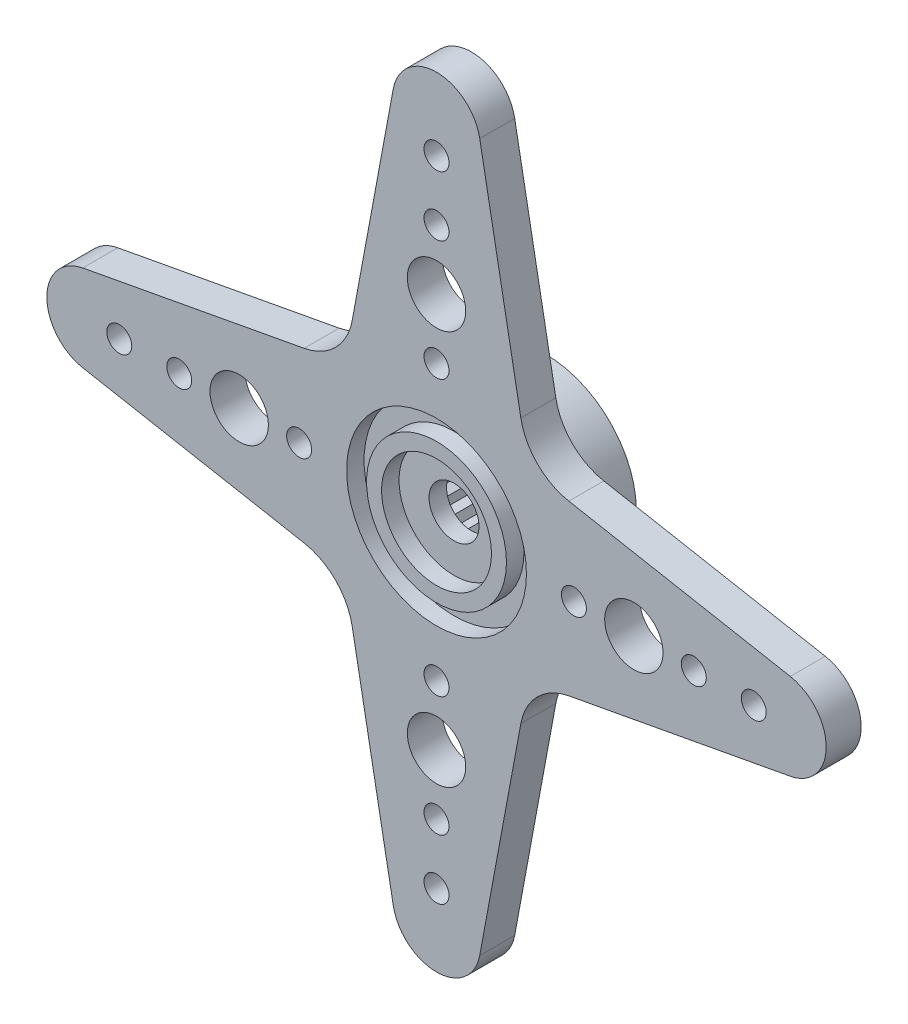
SolidWorks part; units mm, degrees
ref_plane "Front Plane" through (0, 0, 0) normal (0, 0, 1) x (1, 0, 0)
ref_plane "Top Plane" through (0, 0, 0) normal (0, 1, 0) x (1, 0, 0)
ref_plane "Right Plane" through (0, 0, 0) normal (1, 0, 0) x (0, 0, -1)
sketch "Sketch1" plane through (0, 0, 0) normal (0, 0, 1) x (1, 0, 0)
  line L50 (-10.25, 3) -> (-10.5946, 2.7283)
  line L51 (-10.5946, 2.7283) -> (-10.996, 2.9057)
  line L52 (-10.996, 2.9057) -> (-11.2623, 2.5569)
  line L53 (-11.2623, 2.5569) -> (-11.6952, 2.6289)
  line L54 (-11.6952, 2.6289) -> (-11.8664, 2.2248)
  line L55 (-11.8664, 2.2248) -> (-12.3036, 2.1869)
  line L56 (-12.3036, 2.1869) -> (-12.3689, 1.7529)
  line L57 (-12.3689, 1.7529) -> (-12.7829, 1.6075)
  line L58 (-12.7829, 1.6075) -> (-12.7382, 1.1709)
  line L59 (-12.7382, 1.1709) -> (-13.1031, 0.927)
  line L60 (-13.1031, 0.927) -> (-12.9512, 0.5153)
  line L61 (-12.9512, 0.5153) -> (-13.244, 0.1884)
  line L62 (-13.244, 0.1884) -> (-12.9945, -0.1727)
  line L63 (-12.9945, -0.1727) -> (-13.1968, -0.5621)
  line L64 (-13.1968, -0.5621) -> (-12.8654, -0.8498)
  line L65 (-12.8654, -0.8498) -> (-12.9644, -1.2773)
  line L66 (-12.9644, -1.2773) -> (-12.5719, -1.4735)
  line L67 (-12.5719, -1.4735) -> (-12.5615, -1.9123)
  line L68 (-12.5615, -1.9123) -> (-12.1325, -2.0047)
  line L69 (-12.1325, -2.0047) -> (-12.0133, -2.427)
  line L70 (-12.0133, -2.427) -> (-11.5748, -2.4098)
  line L71 (-11.5748, -2.4098) -> (-11.3543, -2.7893)
  line L72 (-11.3543, -2.7893) -> (-10.9339, -2.6636)
  line L73 (-10.9339, -2.6636) -> (-10.626, -2.9763)
  line L74 (-10.626, -2.9763) -> (-10.25, -2.75)
  line L75 (-10.25, -2.75) -> (-9.874, -2.9763)
  line L76 (-9.874, -2.9763) -> (-9.5661, -2.6636)
  line L77 (-9.5661, -2.6636) -> (-9.1456, -2.7893)
  line L78 (-9.1456, -2.7893) -> (-8.9251, -2.4098)
  line L79 (-8.9251, -2.4098) -> (-8.4866, -2.427)
  line L80 (-8.4866, -2.427) -> (-8.3675, -2.0047)
  line L81 (-8.3675, -2.0047) -> (-7.9384, -1.9123)
  line L82 (-7.9384, -1.9123) -> (-7.9281, -1.4735)
  line L83 (-7.9281, -1.4735) -> (-7.5355, -1.2773)
  line L84 (-7.5355, -1.2773) -> (-7.6346, -0.8498)
  line L85 (-7.6346, -0.8498) -> (-7.3031, -0.5621)
  line L86 (-7.3031, -0.5621) -> (-7.5054, -0.1727)
  line L87 (-7.5054, -0.1727) -> (-7.2559, 0.1884)
  line L88 (-7.2559, 0.1884) -> (-7.5487, 0.5153)
  line L89 (-7.5487, 0.5153) -> (-7.3968, 0.927)
  line L90 (-7.3968, 0.927) -> (-7.7617, 1.1709)
  line L91 (-7.7617, 1.1709) -> (-7.717, 1.6075)
  line L92 (-7.717, 1.6075) -> (-8.1311, 1.7529)
  line L93 (-8.1311, 1.7529) -> (-8.1963, 2.1869)
  line L94 (-8.1963, 2.1869) -> (-8.6336, 2.2248)
  line L95 (-8.6336, 2.2248) -> (-8.8047, 2.6289)
  line L96 (-8.8047, 2.6289) -> (-9.2376, 2.5569)
  line L97 (-9.2376, 2.5569) -> (-9.5039, 2.9057)
  line L98 (-9.5039, 2.9057) -> (-9.9053, 2.7283)
  line L99 (-9.9053, 2.7283) -> (-10.25, 3)
  line L100 (-10.25, 3) -> (-10.5946, 2.7283)
  line L101 (-10.5946, 2.7283) -> (-10.996, 2.9057)
  line L102 (-10.996, 2.9057) -> (-11.2623, 2.5569)
  line L103 (-11.2623, 2.5569) -> (-11.6952, 2.6289)
  line L104 (-11.6952, 2.6289) -> (-11.8664, 2.2248)
  line L105 (-11.8664, 2.2248) -> (-12.3036, 2.1869)
  line L106 (-12.3036, 2.1869) -> (-12.3689, 1.7529)
  line L107 (-12.3689, 1.7529) -> (-12.7829, 1.6075)
  line L108 (-12.7829, 1.6075) -> (-12.7382, 1.1709)
  line L109 (-12.7382, 1.1709) -> (-13.1031, 0.927)
  line L110 (-13.1031, 0.927) -> (-12.9512, 0.5153)
  line L111 (-12.9512, 0.5153) -> (-13.244, 0.1884)
  line L112 (-13.244, 0.1884) -> (-12.9945, -0.1727)
  line L113 (-12.9945, -0.1727) -> (-13.1968, -0.5621)
  line L114 (-13.1968, -0.5621) -> (-12.8654, -0.8498)
  line L115 (-12.8654, -0.8498) -> (-12.9644, -1.2773)
  line L116 (-12.9644, -1.2773) -> (-12.5719, -1.4735)
  line L117 (-12.5719, -1.4735) -> (-12.5615, -1.9123)
  line L118 (-12.5615, -1.9123) -> (-12.1325, -2.0047)
  line L119 (-12.1325, -2.0047) -> (-12.0133, -2.427)
  line L120 (-12.0133, -2.427) -> (-11.5748, -2.4098)
  line L121 (-11.5748, -2.4098) -> (-11.3543, -2.7893)
  line L122 (-11.3543, -2.7893) -> (-10.9339, -2.6636)
  line L123 (-10.9339, -2.6636) -> (-10.626, -2.9763)
  line L124 (-10.626, -2.9763) -> (-10.25, -2.75)
  line L125 (-10.25, -2.75) -> (-9.874, -2.9763)
  line L126 (-9.874, -2.9763) -> (-9.5661, -2.6636)
  line L127 (-9.5661, -2.6636) -> (-9.1456, -2.7893)
  line L128 (-9.1456, -2.7893) -> (-8.9251, -2.4098)
  line L129 (-8.9251, -2.4098) -> (-8.4866, -2.427)
  line L130 (-8.4866, -2.427) -> (-8.3675, -2.0047)
  line L131 (-8.3675, -2.0047) -> (-7.9384, -1.9123)
  line L132 (-7.9384, -1.9123) -> (-7.9281, -1.4735)
  line L133 (-7.9281, -1.4735) -> (-7.5355, -1.2773)
  line L134 (-7.5355, -1.2773) -> (-7.6346, -0.8498)
  line L135 (-7.6346, -0.8498) -> (-7.3031, -0.5621)
  line L136 (-7.3031, -0.5621) -> (-7.5054, -0.1727)
  line L137 (-7.5054, -0.1727) -> (-7.2559, 0.1884)
  line L138 (-7.2559, 0.1884) -> (-7.5487, 0.5153)
  line L139 (-7.5487, 0.5153) -> (-7.3968, 0.927)
  line L140 (-7.3968, 0.927) -> (-7.7617, 1.1709)
  line L141 (-7.7617, 1.1709) -> (-7.717, 1.6075)
  line L142 (-7.717, 1.6075) -> (-8.1311, 1.7529)
  line L143 (-8.1311, 1.7529) -> (-8.1963, 2.1869)
  line L144 (-8.1963, 2.1869) -> (-8.6336, 2.2248)
  line L145 (-8.6336, 2.2248) -> (-8.8047, 2.6289)
  line L146 (-8.8047, 2.6289) -> (-9.2376, 2.5569)
  line L147 (-9.2376, 2.5569) -> (-9.5039, 2.9057)
  line L148 (-9.5039, 2.9057) -> (-9.9053, 2.7283)
  line L149 (-9.9053, 2.7283) -> (-10.25, 3)
  circle A0 centre (-10.25, 0) radius 4.5
  dimension "D2" = 9
  dimension "D1" = 0
extrude "Boss-Extrude1" add sketch "Sketch1" against normal blind 3.75 contours A0 L149 L148 L147 L146 L145 L144 L143 L142 L141 L140 L139 L138 L137 L136 L135 L134 L133 L132 L131 L130 L129 L128 L127 L126 L125 L124 L123 L122 L121 L120 L119 L118 L117 L116 L115 L114 L113 L112 L111 L110 L109 L108 L107 L106 L105 L104 L103 L102 L101
sketch "Sketch2" plane through (0, 0, 0) normal (0, 0, 1) x (1, 0, 0)
  circle A0 centre (-10.25, 0) radius 1.25
  circle A1 centre (-10.25, 0) radius 3.5
  circle A2 centre (-10.25, 0) radius 4.5
  dimension "D1" = 7
  dimension "D2" = 2.5
  dimension "D3" = 9
extrude "Boss-Extrude2" add sketch "Sketch2" along normal blind 1.75 contours A2 A1 | A1 A0
sketch "Sketch4" plane through (0, 0, 1.75) normal (0, 0, 1) x (1, 0, 0)
  circle A0 centre (-10.25, 0) radius 3.5
  circle A1 centre (-10.25, 0) radius 2.75
  circle M2 centre (-10.25, 0) radius 1.25
  dimension "D1" = 7
  dimension "D2" = 0.75
extrude "Cut-Extrude1" cut sketch "Sketch4" against normal blind 0.875 contours A1 M2
sketch "Sketch6" plane through (0, 0, 1.75) normal (0, 0, 1) x (1, 0, 0)
  circle A0 centre (-10.25, 0) radius 3.5
  circle A1 centre (-10.25, 0) radius 2.75 construction
  circle A2 centre (-10.25, 0) radius 4.5
  circle M2 centre (-10.25, 0) radius 4.5
  dimension "D1" = 0.75
  dimension "D2" = 9
extrude "Cut-Extrude2" cut sketch "Sketch6" against normal blind 0.875 contours A0 M2
sketch "Sketch7" [suppressed] plane through (0, 0, 1.75) normal (0, 0, 1) x (1, 0, 0)
  circle A0 centre (-10.25, 0) radius 10.5
  circle A1 centre (-10.25, 0) radius 4.5
  dimension "D1" = 21
extrude "Boss-Extrude3" [suppressed] add sketch "Sketch7" against normal blind 1.75
sketch "Sketch9" [suppressed] plane through (0, 0, 1.75) normal (0, 0, 1) x (1, 0, 0)
  line L0 (-10.25, 0) -> (-10.25, 11.6833) construction
  circle A0 centre (-10.25, 7.875) radius 0.625
  circle A1 centre (-14.125, 7.875) radius 0.625
  circle A2 centre (-10.25, 0) radius 10.5 construction
  circle A3 centre (-6.375, 7.875) radius 0.625
  dimension "D1" = 2
  dimension "D2" = 1.25
  dimension "D3" = 1.25
  dimension "D4" = 2.625
extrude "Cut-Extrude3" [suppressed] cut sketch "Sketch9" against normal through all
pattern_circular "CirPattern1" [suppressed] count 4 over 360
chamfer "Chamfer1" [suppressed] distance 1 angle 30
sketch "Sketch10" plane through (0, 0, 1.75) normal (0, 0, 1) x (1, 0, 0)
  line L0 (-10.25, 0) -> (-10.25, 9.0053) construction
  line L1 (-10.25, 0) -> (0.0732, 10.3232) construction
  line L2 (-10.25, 0) -> (1.1009, 0) construction
  line L3 (-8.0869, 17.7016) -> (-6.0299, 6.622)
  line L4 (-3.6279, 4.2201) -> (7.4516, 2.163)
  line L5 (7.4516, -2.163) -> (-3.6279, -4.2201)
  line L6 (-6.0299, -6.622) -> (-8.0869, -17.7016)
  line L7 (-12.413, -17.7016) -> (-14.47, -6.622)
  line L8 (-16.872, -4.2201) -> (-27.9515, -2.163)
  line L9 (-27.9515, 2.163) -> (-16.872, 4.2201)
  line L10 (-14.47, 6.622) -> (-12.413, 17.7016)
  arc A0 (-8.0869, 17.7016) -> (-10.25, 19.5) centre (-10.25, 17.3) ccw
  arc A1 (7.4516, -2.163) -> (7.4516, 2.163) centre (7.05, 0) ccw
  arc A2 (-6.0299, 6.622) -> (-3.6279, 4.2201) centre (-3.0803, 7.1697) ccw
  circle A3 centre (-10.25, 15.875) radius 0.625
  circle A4 centre (-10.25, 12.875) radius 0.625
  circle A5 centre (-10.25, 9.875) radius 0.625
  circle A6 centre (-10.25, 6.875) radius 0.625
  arc A7 (7.4516, -2.163) -> (9.25, 0) centre (7.05, 0) ccw
  circle A8 centre (5.625, 0) radius 0.625
  circle A9 centre (2.625, 0) radius 0.625
  circle A10 centre (-0.375, 0) radius 0.625
  circle A11 centre (-3.375, 0) radius 0.625
  arc A12 (-3.6279, -4.2201) -> (-6.0299, -6.622) centre (-3.0803, -7.1697) ccw
  arc A13 (-12.413, -17.7016) -> (-8.0869, -17.7016) centre (-10.25, -17.3) ccw
  arc A14 (-12.413, -17.7016) -> (-10.25, -19.5) centre (-10.25, -17.3) ccw
  circle A15 centre (-10.25, -15.875) radius 0.625
  circle A16 centre (-10.25, -12.875) radius 0.625
  circle A17 centre (-10.25, -9.875) radius 0.625
  circle A18 centre (-10.25, -6.875) radius 0.625
  arc A19 (-14.47, -6.622) -> (-16.872, -4.2201) centre (-17.4196, -7.1697) ccw
  arc A20 (-27.9515, 2.163) -> (-27.9515, -2.163) centre (-27.5499, 0) ccw
  arc A21 (-27.9515, 2.163) -> (-29.7499, 0) centre (-27.5499, 0) ccw
  circle A22 centre (-26.1249, 0) radius 0.625
  circle A23 centre (-23.1249, 0) radius 0.625
  circle A24 centre (-20.1249, 0) radius 0.625
  circle A25 centre (-17.1249, 0) radius 0.625
  arc A26 (-16.872, 4.2201) -> (-14.47, 6.622) centre (-17.4196, 7.1697) ccw
  arc A27 (-8.0869, 17.7016) -> (-12.413, 17.7016) centre (-10.25, 17.3) ccw
  circle A28 centre (-10.25, 0) radius 4.5
  point P1 (-10.25, 0)
  point P10 (-5.6538, 4.5962)
  point P20 (-5.6538, 4.5962)
  point P21 (-10.25, 19.5)
  point P84 (-10.25, 0)
  circle M4 centre (-10.25, 0) radius 3.5
  dimension "D2" = 19.5
  dimension "D3" = 19.5
  dimension "D4" = 4.4
  dimension "D5" = 4.4
  dimension "D7" = 3
  dimension "D8" = 1.25
  dimension "D9" = 3
  dimension "D1" = 45
  dimension "D6" = 6.5
  dimension "D10" = 4
  dimension "D11" = 4
extrude "Boss-Extrude4" add sketch "Sketch10" against normal blind 1.75 contours A0 A27 L10 A26 L9 A20 L8 A19 L7 A13 L6 A12 L5 A1 L4 A2 L3 A3 A4 A5 A6 A8 A9 A10 A11 A15 A16 A17 A18 A22 A23 M4
chamfer "Chamfer2" distance 1 angle 30 1 edges at (-5.75, 0, 0)
sketch "Sketch11" [suppressed] plane through (0, 0, 1.75) normal (0, 0, 1) x (1, 0, 0)
  line L0 (-10.25, 0) -> (-10.25, 17.5605) construction
  line L1 (-10.25, 0) -> (4.9579, 8.7803) construction
  line L2 (-10.25, 0) -> (4.9579, -8.7803) construction
  line L3 (-10.25, 0) -> (-10.25, -17.5605) construction
  line L4 (-10.25, 0) -> (-25.4578, -8.7803) construction
  line L5 (-10.25, 0) -> (-25.4578, 8.7803) construction
  line L6 (-10.25, 0) -> (-3.969, 10.8789) construction
  line L7 (-10.25, 0) -> (2.312, 0) construction
  line L8 (-10.25, 0) -> (-3.969, -10.8789) construction
  line L9 (-10.25, 0) -> (-16.5309, -10.8789) construction
  line L10 (-10.25, 0) -> (-22.8119, 0) construction
  line L11 (-10.25, 0) -> (-16.5309, 10.8789) construction
  line L12 (-8.5769, 14.5133) -> (-6.25, 6.9282)
  line L13 (-6.25, 6.9282) -> (1.4824, 8.7055)
  line L14 (3.1554, 5.8077) -> (-2.25, 0)
  line L15 (-2.25, 0) -> (3.1554, -5.8077)
  line L16 (1.4824, -8.7055) -> (-6.25, -6.9282)
  line L17 (-6.25, -6.9282) -> (-8.5769, -14.5133)
  line L18 (-11.923, -14.5133) -> (-14.25, -6.9282)
  line L19 (-14.25, -6.9282) -> (-21.9823, -8.7055)
  line L20 (-23.6553, -5.8077) -> (-18.25, 0)
  line L21 (-18.25, 0) -> (-23.6553, 5.8077)
  line L22 (-21.9823, 8.7055) -> (-14.25, 6.9282)
  line L23 (-14.25, 6.9282) -> (-11.923, 14.5133)
  circle A0 centre (-10.25, 0) radius 4.5
  arc A1 (-8.5769, 14.5133) -> (-10.25, 15.75) centre (-10.25, 14) ccw
  arc A2 (3.3899, 7.875) -> (1.4824, 8.7055) centre (1.8744, 7) ccw
  circle A4 centre (-10.25, 13.375) radius 0.625
  circle A5 centre (-10.25, 10.375) radius 0.625
  circle A6 centre (-10.25, 7.375) radius 0.625
  circle A7 centre (1.3331, 6.6875) radius 0.625
  arc A8 (3.1554, 5.8077) -> (3.3899, 7.875) centre (1.8744, 7) ccw
  circle A9 centre (-1.2649, 5.1875) radius 0.625
  circle A10 centre (-3.863, 3.6875) radius 0.625
  arc A11 (3.3899, -7.875) -> (3.1554, -5.8077) centre (1.8744, -7) ccw
  circle A12 centre (1.3331, -6.6875) radius 0.625
  arc A13 (1.4824, -8.7055) -> (3.3899, -7.875) centre (1.8744, -7) ccw
  circle A14 centre (-1.2649, -5.1875) radius 0.625
  circle A15 centre (-3.863, -3.6875) radius 0.625
  arc A16 (-10.25, -15.75) -> (-8.5769, -14.5133) centre (-10.25, -14) ccw
  circle A17 centre (-10.25, -13.375) radius 0.625
  arc A18 (-11.923, -14.5133) -> (-10.25, -15.75) centre (-10.25, -14) ccw
  circle A19 centre (-10.25, -10.375) radius 0.625
  circle A20 centre (-10.25, -7.375) radius 0.625
  arc A21 (-23.8899, -7.875) -> (-21.9823, -8.7055) centre (-22.3743, -7) ccw
  circle A22 centre (-21.833, -6.6875) radius 0.625
  arc A23 (-23.6553, -5.8077) -> (-23.8899, -7.875) centre (-22.3743, -7) ccw
  circle A24 centre (-19.235, -5.1875) radius 0.625
  circle A25 centre (-16.6369, -3.6875) radius 0.625
  arc A26 (-23.8899, 7.875) -> (-23.6553, 5.8077) centre (-22.3743, 7) ccw
  circle A27 centre (-21.833, 6.6875) radius 0.625
  arc A28 (-21.9823, 8.7055) -> (-23.8899, 7.875) centre (-22.3743, 7) ccw
  circle A29 centre (-19.235, 5.1875) radius 0.625
  circle A30 centre (-16.6369, 3.6875) radius 0.625
  arc A31 (-10.25, 15.75) -> (-11.923, 14.5133) centre (-10.25, 14) ccw
  point P5 (-10.25, 0)
  point P12 (-10.25, 0)
  point P20 (-10.25, 0)
  point P22 (-6.25, 6.9282)
  point P26 (-10.25, 15.75)
  point P27 (3.3899, 7.875)
  point P102 (-10.25, 0)
  dimension "D4" = 15.75
  dimension "D5" = 15.75
  dimension "D6" = 3.5
  dimension "D7" = 3.5
  dimension "D9" = 1.25
  dimension "D10" = 1.75
  dimension "D2" = 30
  dimension "D8" = 8
  dimension "D11" = 3
  dimension "D1" = 6
  dimension "D3" = 6
  dimension "D12" = 6
extrude "Boss-Extrude5" [suppressed] add sketch "Sketch11" against normal blind 1.75 contours A1 A31 L23 L22 A28 A26 L21 L20 A23 A21 L19 L18 A18 A16 L17 L16 A13 A11 L15 L14 A8 A2 L13 L12 A0 A4 A5 A6 A7 A9 A10 A12 A14 A15 A17 A19 A20
chamfer "Chamfer4" [suppressed] distance 1 angle 30
sketch "Sketch12" [suppressed] plane through (0, 0, 0.875) normal (0, 0, 1) x (1, 0, 0)
  circle A0 centre (-10.25, 0) radius 1.25
  circle A1 centre (-10.25, 0) radius 5
extrude "Boss-Extrude6" [suppressed] add sketch "Sketch12" along normal blind 0.125
sketch "Sketch14" [suppressed] plane through (0, 0, 1) normal (0, 0, 1) x (1, 0, 0)
  line L0 (-10.25, 0) -> (-28.2499, 0) construction
  line L1 (-10.25, -6) -> (-28.2499, -6)
  line L2 (-10.25, 6) -> (-28.2499, 6)
  arc A0 (-10.25, -6) -> (-10.25, 6) centre (-10.25, 0) ccw
  arc A1 (-28.2499, 6) -> (-28.2499, -6) centre (-28.2499, 0) ccw
  point P4 (-19.2499, 0)
  dimension "D1" = 12
  dimension "D2" = 29.9999
extrude "Boss-Extrude7" [suppressed] add sketch "Sketch14" along normal blind 3
sketch "Sketch16" [suppressed] plane through (0, 0, 1) normal (0, 0, -1) x (-1, 0, 0)
  line L0 (25.9999, 0) -> (30.4999, 0) construction
  line L1 (25.9999, 2.75) -> (30.4999, 2.75)
  line L2 (25.9999, -2.75) -> (30.4999, -2.75)
  arc A0 (25.9999, 2.75) -> (25.9999, -2.75) centre (25.9999, 0) ccw
  arc A1 (30.4999, -2.75) -> (30.4999, 2.75) centre (30.4999, 0) ccw
  arc A10 (28.2499, -6) -> (28.2499, 6) centre (28.2499, 0) ccw construction
  point P3 (28.2499, 0)
  point P8 (34.2499, 0)
  point P9 (33.2499, 0)
  dimension "D2" = 10
  dimension "D3" = 1
  dimension "D1" = 5.5
extrude "Boss-Extrude8" [suppressed] add sketch "Sketch16" along normal blind 2.75 contours L1 A1 L2 A0
sketch "Sketch17" [suppressed] plane through (0, 0, -1.75) normal (0, 0, -1) x (-1, 0, 0)
  circle A0 centre (30.7499, 0) radius 1.5
  circle A1 centre (25.7499, 0) radius 1.5
  arc A5 (28.2499, -6) -> (28.2499, 6) centre (28.2499, 0) ccw construction
  dimension "D1" = 3
  dimension "D2" = 3
  dimension "D3" = 2
  dimension "D4" = 2
extrude "Cut-Extrude4" [suppressed] cut sketch "Sketch17" against normal through all
sketch "Sketch18" [suppressed] plane through (0, 0, 1) normal (0, 0, -1) x (-1, 0, 0)
  circle A0 centre (10.25, 0) radius 3
  dimension "D1" = 6
extrude "Cut-Extrude5" [suppressed] cut sketch "Sketch18" against normal through all
sketch "Sketch19" [suppressed] plane through (0, 0, 1.5) normal (0, 0, 1) x (1, 0, 0)
  line L0 (-35.7499, 0) -> (15.25, 0) construction
  line L1 (-9.625, 5.9674) -> (14.1146, 3.481)
  line L2 (14.1146, -3.481) -> (-9.625, -5.9674)
  line L3 (-10.25, 0) -> (-10.25, 10.691) construction
  line L4 (-34.6145, -3.481) -> (-10.875, -5.9674)
  line L5 (-10.875, 5.9674) -> (-34.6145, 3.481)
  circle A0 centre (-10.25, 0) radius 6
  arc A1 (14.1146, -3.481) -> (14.1146, 3.481) centre (13.75, 0) ccw
  circle A2 centre (14.625, 0) radius 0.625
  circle A3 centre (11.375, 0) radius 0.625
  circle A4 centre (8.125, 0) radius 0.625
  circle A5 centre (4.875, 0) radius 0.625
  circle A6 centre (1.625, 0) radius 0.625
  circle A7 centre (-22.1249, 0) radius 0.625
  circle A8 centre (-25.3749, 0) radius 0.625
  circle A9 centre (-28.6249, 0) radius 0.625
  circle A10 centre (-31.8749, 0) radius 0.625
  circle A11 centre (-35.1249, 0) radius 0.625
  arc A12 (-34.6145, -3.481) -> (-34.6145, 3.481) centre (-34.2499, 0) cw
  point P37 (-10.25, -6)
  circle M5 centre (-10.25, 0) radius 5
  circle M6 centre (-10.25, 0) radius 1.25
  dimension "D1" = 12
  dimension "D2" = 7
  dimension "D4" = 1.25
  dimension "D5" = 2
  dimension "D3" = 27.4999
  dimension "D6" = 5
extrude "Boss-Extrude9" [suppressed] add sketch "Sketch19" along normal blind 2.5 contours A12 L4 A0 L5 A10 A8 A7 A9 A11 | A0 M5 | M5 M6 | L2 A1 L1 A0 A6 A5 A4 A3 A2
sketch "Sketch20" [suppressed] plane through (0, 0, 4) normal (0, 0, 1) x (1, 0, 0)
  arc A0 (-9.625, 5.9674) -> (-10.875, 5.9674) centre (-10.25, 0) ccw construction
  circle A1 centre (-10.25, 0) radius 4
  circle A2 centre (-10.25, 0) radius 6
  point P5 (-10.25, 4)
  point P7 (-10.25, -4)
  dimension "D1" = 2
extrude "Boss-Extrude10" [suppressed] add sketch "Sketch20" along normal blind 1
sketch "Sketch21" [suppressed] plane through (0, 0, 4) normal (0, 0, 1) x (1, 0, 0)
  circle A0 centre (-10.25, 0) radius 4 construction
  circle A1 centre (-10.25, 0) radius 4
  circle A2 centre (-10.25, 0) radius 3.25
  dimension "D1" = 0.75
extrude "Boss-Extrude11" [suppressed] add sketch "Sketch21" along normal offset from surface (0.5 mm away) 0.5
sketch "Sketch22" [suppressed] plane through (0, 0, 4) normal (0, 0, 1) x (1, 0, 0)
  circle A0 centre (-10.25, 0) radius 3.25
extrude "Cut-Extrude6" [suppressed] cut sketch "Sketch22" against normal offset from surface (3 mm away) 1 contours A0
chamfer "Chamfer5" [suppressed] distance 0.75 angle 45
ref_plane "Plane1" [suppressed] through (0, 4.5, 0) normal (0, 1, 0) x (1, 0, 0)
ref_plane "Plane3" [suppressed] through (0, 0.5, 0) normal (0, 1, 0) x (1, 0, 0)
sketch "Sketch26" [suppressed] plane through (0, 0.5, 0) normal (0, 1, 0) x (1, 0, 0)
  line L0 (-17.4408, -4) -> (-16.1908, -5)
  line L1 (-10.875, -4) -> (-34.6145, -4) construction
  line L2 (-16.1908, -5) -> (-15.6228, -4)
  line L3 (-15.6228, -4) -> (-17.4408, -4)
  line L4 (-16.25, -5) -> (-4.25, -5) construction
  dimension "D1" = 1.25
extrude "Boss-Extrude15" [suppressed] add sketch "Sketch26" against normal blind 1
ref_plane "Plane4" [suppressed] through (0, 5, 0) normal (0, 1, 0) x (1, 0, 0)
sketch "Sketch27" [suppressed] plane through (0, 5, 0) normal (0, 1, 0) x (1, 0, 0)
  line L0 (-17.4408, -4) -> (-13.2508, -4)
  line L1 (-16.1908, -5) -> (-13.2508, -5)
  line L3 (-17.4408, -4) -> (-16.1908, -5)
  line L4 (-16.1908, -5) -> (-15.6228, -4)
  line L5 (-15.6228, -4) -> (-17.4408, -4)
  line L6 (-17.4408, -4) -> (-16.1908, -5)
  line L10 (-13.2508, -5) -> (-13.2508, -4)
  dimension "D1" = 0
extrude "Boss-Extrude16" [suppressed] add sketch "Sketch27" against normal blind 1 contours L6 L1 L10 L0
mirror "Mirror1" [suppressed] about plane through (0, 0, 0) normal (0, 1, 0)
ref_plane "Plane5" [suppressed] through (-10.25, 0, 0) normal (1, 0, 0) x (0, 0, -1)
mirror "Mirror2" [suppressed] about plane through (-10.25, 0, 0) normal (1, 0, 0)
ref_plane "Plane6" [suppressed] through (0, 0, 2.75) normal (0, 0, 1) x (1, 0, 0)
mirror "Mirror3" [suppressed] about plane through (0, 0, 2.75) normal (0, 0, 1)
mirror "Mirror4" [suppressed] about plane through (-10.25, 0, 0) normal (1, 0, 0)
sketch "Sketch29" [suppressed] plane through (0, -5, 0) normal (0, -1, 0) x (1, 0, 0)
  line L0 (-15.25, 1.5) -> (-5.25, 1.5) construction
  line L1 (-13.2508, 0.5) -> (-7.2491, 0.5)
  line L2 (-13.2508, 0.5) -> (-13.2508, 1.5)
  line L3 (-13.2508, 1.5) -> (-7.2491, 1.5)
  line L4 (-7.2491, 0.5) -> (-7.2491, 1.5)
  line L5 (-7.2491, 0.5) -> (-7.2491, 1.5) construction
extrude "Boss-Extrude17" [suppressed] add sketch "Sketch29" against normal up to surface (1 mm away)
sketch "Sketch31" [suppressed] plane through (0, 0, 5) normal (0, 0, 1) x (1, 0, 0)
  line L1 (-19.5679, -7.6233) -> (-0.9321, -7.6233)
  line L2 (-19.5679, -7.6233) -> (-19.5679, 7.6233)
  line L3 (-19.5679, 7.6233) -> (-0.9321, 7.6233)
  line L4 (-0.9321, -7.6233) -> (-0.9321, 7.6233)
  line L5 (-19.5679, -7.6233) -> (-0.9321, 7.6233) construction
  line L6 (-19.5679, 7.6233) -> (-0.9321, -7.6233) construction
  point P0 (-10.25, 0)
  point P1 (-10.25, 0)
extrude "Cut-Extrude7" [suppressed] cut sketch "Sketch31" against normal blind 0.7493
ref_plane "Plane7" through (-10.25, 0, 0) normal (1, 0, 0) x (0, 0, -1)
sketch "Sketch32" plane through (0, 0, 0) normal (0, 0, -1) x (-1, 0, 0)
  circle A0 centre (20.1249, 0) radius 1.4605
  circle A1 centre (10.25, 0) radius 9.875
  circle A2 centre (10.25, -9.875) radius 1.4605
  circle A3 centre (0.375, 0) radius 1.4605
  circle A4 centre (10.25, 9.875) radius 1.4605
  point P15 (10.25, 0)
  dimension "D1" = 2.921
  dimension "D2" = 4
extrude "Cut-Extrude8" cut sketch "Sketch32" against normal through all contours A0 | A2 | A3 | A4
